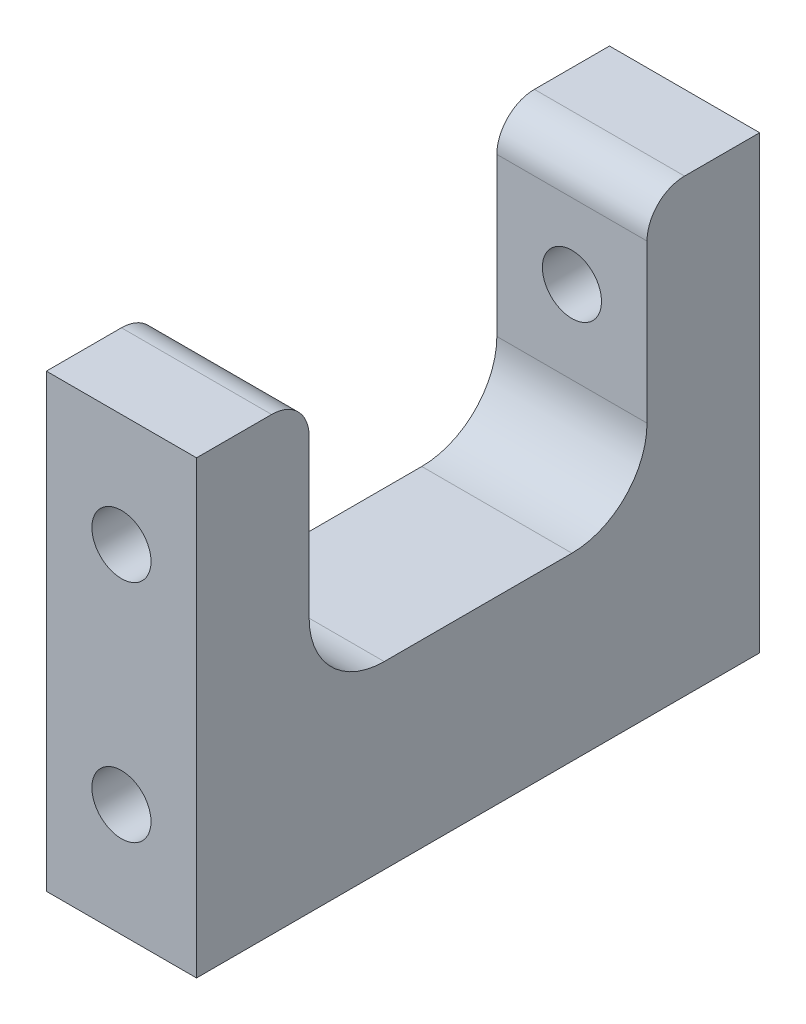
SolidWorks part; units mm, degrees
material "7075-T6 (SN)"
ref_plane "Front Plane" through (0, 0, 0) normal (0, 0, 1) x (1, 0, 0)
ref_plane "Top Plane" through (0, 0, 0) normal (0, 1, 0) x (1, 0, 0)
ref_plane "Right Plane" through (0, 0, 0) normal (1, 0, 0) x (0, 0, -1)
sketch "Sketch1" plane through (0, 0, 0) normal (0, 0, 1) x (1, 0, 0)
  line L1 (-3.175, -9.525) -> (3.175, -9.525)
  line L2 (-3.175, -9.525) -> (-3.175, 9.525)
  line L3 (-3.175, 9.525) -> (3.175, 9.525)
  line L4 (3.175, -9.525) -> (3.175, 9.525)
  line L5 (-3.175, -9.525) -> (3.175, 9.525) construction
  line L6 (-3.175, 9.525) -> (3.175, -9.525) construction
  point P0 (0, 0)
  dimension "D1" = 6.35
  dimension "D2" = 19.05
extrude "Boss-Extrude2" add sketch "Sketch1" along normal blind 23.8125
sketch "Sketch2" plane through (3.175, 0, 0) normal (1, 0, 0) x (0, 0, -1)
  line L0 (-23.8125, 9.525) -> (0, 9.525) construction
  line L1 (-19.05, 9.525) -> (-4.7625, 9.525)
  line L2 (-19.05, 9.525) -> (-19.05, -1.905)
  line L3 (-19.05, -1.905) -> (-4.7625, -1.905)
  line L4 (-4.7625, 9.525) -> (-4.7625, -1.905)
  line L8 (-11.9062, -1.905) -> (-11.9062, -5.59) construction
  line L10 (0, 9.525) -> (0, -9.525) construction
  line L11 (-23.8125, 9.525) -> (-23.8125, -9.525) construction
  dimension "D1" = 14.2875
  dimension "D2" = 11.43
extrude "WHEEL-SLOT" cut sketch "Sketch2" against normal through all
hole_wizard "M3x0.5 Tapped Hole1" positions "Sketch3" profile "Sketch4" tap size "M3x0.5" standard "ANSI Metric"
sketch "Sketch3" plane through (0, 0, 23.8125) normal (0, 0, 1) x (1, 0, 0)
  line L2 (0, 0) -> (1.8775, 0) construction
  line L4 (0, 0) -> (0, 1.9661) construction
  line L5 (-3.175, -9.525) -> (3.175, -9.525) construction
  point P0 (0, -4.7625)
  point P2 (0, 4.7625)
  dimension "D1" = 9.525
  dimension "D2" = 4.7625
cosmetic thread "Hole Thread3" parameters "D1"=2.286, "D2"=3
cosmetic thread "Hole Thread4" parameters "D1"=2.286, "D2"=3
sketch "Sketch4" plane through (0, -4.7625, 23.8125) normal (1, 0, 0) x (0, -1, 0)
  line L0 (0, 0) -> (0, 10.6571)
  line L1 (0, 10.6571) -> (1.25, 9.906)
  line L2 (1.25, 9.906) -> (1.25, 0)
  line L5 (1.25, 0) -> (0, 0)
  line L10 (0, 10.6571) -> (-1.25, 9.906) construction
  line L11 (0, -6.35) -> (0, 107.95) construction
  dimension "Tap Drill Dia." = 2.5
  dimension "Tap Drill Depth" = 9.906
  dimension "Drill Angle" = 118
ref_plane "PART-MIDPLANE" through (0, 0, 11.9062) normal (0, 0, 1) x (1, 0, 0)
mirror "M3-TAPPED-MIR" about plane through (0, 0, 11.9062) normal (0, 0, 1) of "M3x0.5 Tapped Hole1"
fillet "Fillet1" radius 3.175 2 edges at (0, -1.905, 19.05) (0, -1.905, 4.7625)
fillet "Fillet2" radius 1.5875 2 edges at (0, 9.525, 19.05) (0, 9.525, 4.7625)
